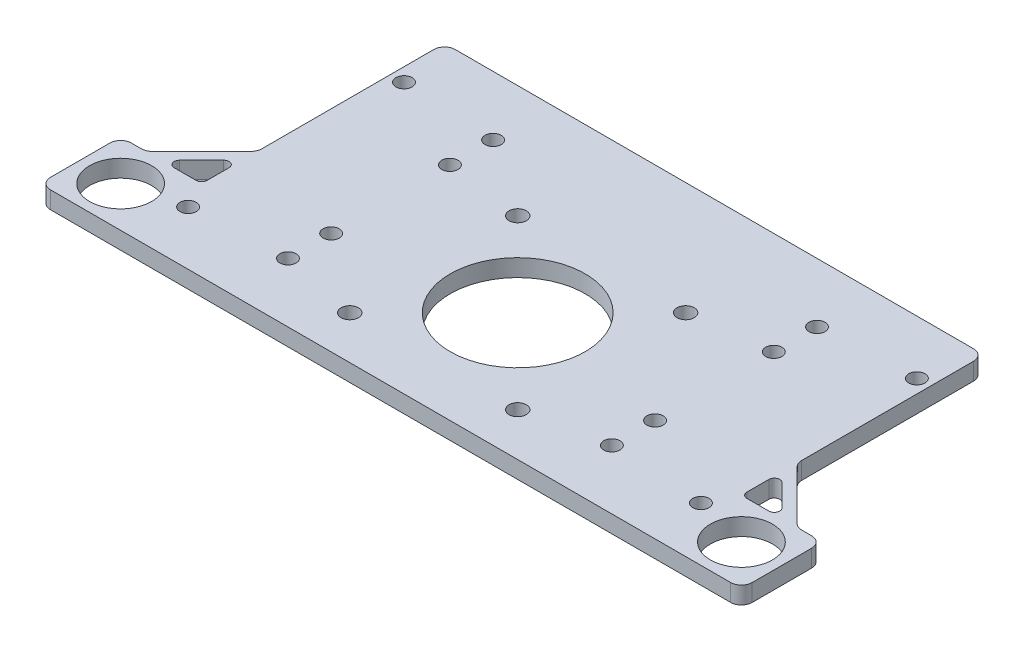
SolidWorks part; units mm, degrees
ref_plane "前视基准面" through (0, 0, 0) normal (0, 0, 1) x (1, 0, 0)
ref_plane "上视基准面" through (0, 0, 0) normal (0, 1, 0) x (1, 0, 0)
ref_plane "右视基准面" through (0, 0, 0) normal (1, 0, 0) x (0, 0, -1)
other "Configuration Table"
sketch "草图1" plane through (0, 0, 0) normal (0, 1, 0) x (1, 0, 0)
  line L0 (0, 30) -> (0, -30) construction
  line L1 (-50, 30) -> (50, 30)
  line L2 (-50, 30) -> (-50, -30)
  line L3 (-50, -30) -> (50, -30)
  line L4 (50, 30) -> (50, -30)
  line L5 (-50, -30) -> (-65, -30)
  line L6 (-50, 0) -> (50, 0) construction
  line L7 (-65, -30) -> (-65, -15)
  line L8 (-65, -15) -> (-50, -15)
  line L9 (-50, -15) -> (-50, -30)
  line L10 (50, -15) -> (50, -30)
  line L11 (65, -15) -> (50, -15)
  line L12 (65, -30) -> (65, -15)
  line L13 (50, -30) -> (65, -30)
  line L14 (-57.5, -15) -> (-50, -7.5)
  line L16 (-60.3284, -15) -> (-50, -4.6716)
  line L17 (-60.3284, -15) -> (-57.5, -15)
  line L18 (-50, -4.6716) -> (-50, -7.5)
  line L19 (60.3284, -15) -> (50, -4.6716)
  line L20 (60.3284, -15) -> (57.5, -15)
  line L21 (57.5, -15) -> (50, -7.5)
  line L22 (50, -4.6716) -> (50, -7.5)
  dimension "D1" = 60
  dimension "D2" = 100
  dimension "D3" = 15
  dimension "D4" = 15
  dimension "D5" = 45
  dimension "D6" = 2
extrude "凸台-拉伸1" add sketch "草图1" along normal blind 3.2 contours L8 L7 L5 L2 | L4 L1 L2 L3 | L16 L8 L14 L2 | L4 L13 L12 L11 | L21 L11 L19 L4
sketch "草图2" plane through (0, 3.2, 0) normal (0, 1, 0) x (1, 0, 0)
  line L0 (0, 0) -> (0, -30) construction
  line L1 (-65, -22.5) -> (-50, -22.5) construction
  line L2 (0, 0) -> (0, 30) construction
  line L3 (-65, -30) -> (-65, -15) construction
  line L4 (-15.5563, -22) -> (15.5563, -22) construction
  line L5 (0, -6.4437) -> (0, -22) construction
  line L6 (-50, 0) -> (50, 0) construction
  line L7 (-65, -30) -> (-50, -30)
  line L8 (-57.5, -30) -> (-57.5, -22.5) construction
  line L9 (-47.5, 30) -> (-47.5, -30) construction
  line L10 (-50, -20) -> (50, -20) construction
  line L11 (-50, 20) -> (50, 20) construction
  line L12 (-50, -7.5) -> (-50, -15) construction
  line L13 (-50, -15) -> (-50, -30) construction
  line L14 (65, -30) -> (-65, -30) construction
  line L15 (50, -7.5) -> (50, -15) construction
  line L16 (50, -15) -> (50, -30) construction
  line L17 (-50, -30) -> (50, -30)
  line L18 (0, -20.4671) -> (0, 20.4671) construction
  line L19 (-50, 30) -> (-50, -30) construction
  line L20 (-50, 30) -> (50, 30)
  line L21 (-95.0755, 0) -> (95.0755, 0) construction
  line L22 (50, 30) -> (50, -4.6716) construction
  line L23 (30, -24) -> (30, -16) construction
  circle A0 centre (0, -6.4437) radius 12.5
  circle A1 centre (15.5563, -22) radius 1.6
  circle A2 centre (15.5563, 9.1127) radius 1.6
  circle A3 centre (-15.5563, 9.1127) radius 1.6
  circle A4 centre (-15.5563, -22) radius 1.6
  circle A5 centre (-47.5, 20) radius 1.5
  circle A6 centre (-47.5, -20) radius 1.5
  circle A7 centre (47.5, -20) radius 1.5
  circle A8 centre (47.5, 20) radius 1.5
  circle A17 centre (-57.5, -22.5) radius 5.75
  circle A18 centre (57.5, -22.5) radius 5.75
  circle A19 centre (30, 19) radius 1.5
  circle A20 centre (30, 11) radius 1.5
  circle A21 centre (-30, 11) radius 1.5
  circle A22 centre (-30, 19) radius 1.5
  circle A23 centre (30, -11) radius 1.5
  circle A24 centre (30, -19) radius 1.5
  circle A25 centre (-30, -19) radius 1.5
  circle A26 centre (-30, -11) radius 1.5
  point P6 (0, 30)
  point P62 (-50, 0)
  point P67 (0, -30)
  dimension "D1" = 25
  dimension "D2" = 3.2
  dimension "D6" = 3
  dimension "D7" = 3
  dimension "D12" = 20
  dimension "D15" = 11.5
  dimension "D18" = 3
  dimension "D19" = 3
  dimension "D13" = 3
  dimension "D14" = 3
  dimension "D3" = 22
  dimension "D5" = 8
  dimension "D8" = 20
  dimension "D9" = 20
  dimension "D10" = 2.5
  dimension "D11" = 20
  dimension "D16" = 49
  dimension "D17" = 41
  dimension "D20" = 11
  dimension "D21" = 19
  dimension "D22" = 17.5
  dimension "D23" = 95
  dimension "D24" = 40
  dimension "D4" = 4
extrude "切除-拉伸1" cut sketch "草图2" against normal up to surface (3.2 mm away) contours A17 | A18 up to face at (52.5, 0, 12.5)
fillet "圆角1" radius 2 10 edges at (65, 1.6, 30) (65, 1.6, 15) (-65, 1.6, 30) (-65, 1.6, 15) (-50, 1.6, -30) (50, 1.6, -30) (60.3284, 1.6, 15) (50, 1.6, 4.6716) (-60.3284, 1.6, 15) (-50, 1.6, 4.6716)
fillet "圆角2" radius 1 6 edges at (-50, 1.6, 15) (-50, 1.6, 7.5) (-57.5, 1.6, 15) (50, 1.6, 15) (57.5, 1.6, 15) (50, 1.6, 7.5)
